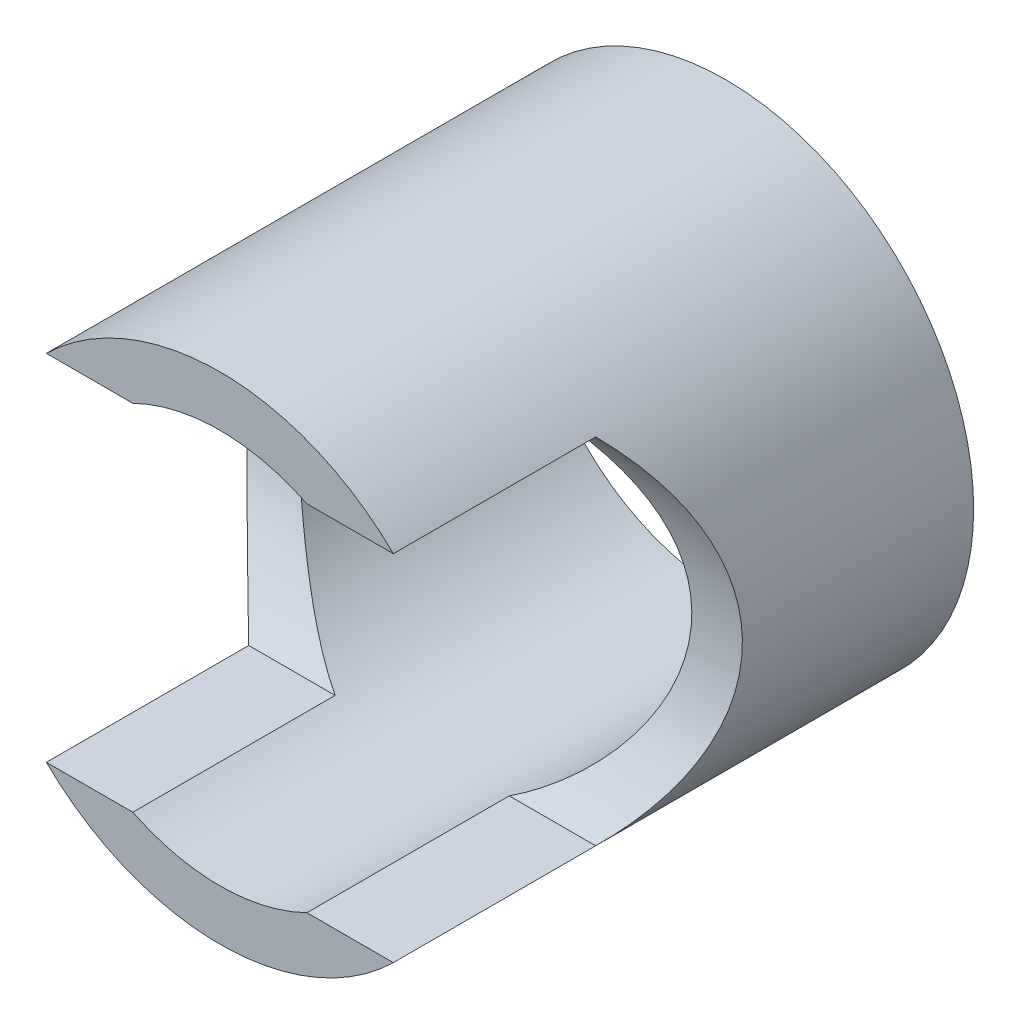
SolidWorks part; units mm, degrees
ref_plane "Front Plane" through (0, 0, 0) normal (0, 0, 1) x (1, 0, 0)
ref_plane "Top Plane" through (0, 0, 0) normal (0, 1, 0) x (1, 0, 0)
ref_plane "Right Plane" through (0, 0, 0) normal (1, 0, 0) x (0, 0, -1)
sketch "Sketch1" plane through (0, 0, 0) normal (0, 0, 1) x (1, 0, 0)
  circle A0 centre (0, 0) radius 3.9
  circle A1 centre (0, 0) radius 4.9
  dimension "D1" = 7.8
  dimension "D2" = 9.8
extrude "Boss-Extrude1" add sketch "Sketch1" along normal blind 10
ref_plane "Plane1" through (4.9, 0, 0) normal (1, 0, 0) x (0, 0, -1)
sketch "Sketch3" plane through (4.9, 0, 0) normal (1, 0, 0) x (0, 0, -1)
  line L2 (-10, 3.5) -> (-10, -3.5)
  line L3 (-10, 3.5) -> (-6, 3.5)
  line L4 (-10, -3.5) -> (-6, -3.5)
  arc A0 (-6, 3.5) -> (-6, -3.5) centre (-9.5707, 0) cw
  dimension "D1" = 7
  dimension "D3" = 5
  dimension "D2" = 4
extrude "Cut-Extrude1" cut sketch "Sketch3" against normal blind 10
